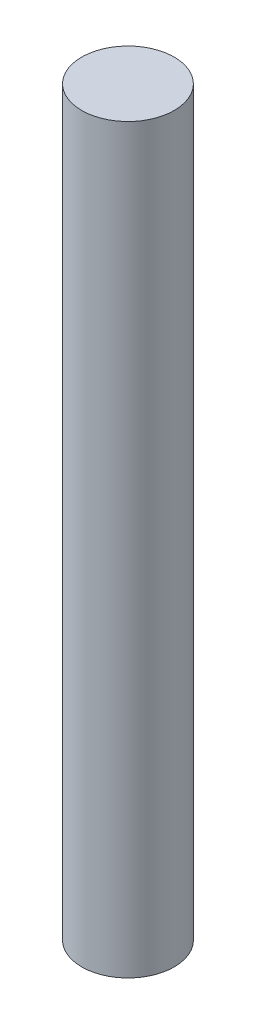
SolidWorks part; units mm, degrees
ref_plane "前视基准面" through (0, 0, 0) normal (0, 0, 1) x (1, 0, 0)
ref_plane "上视基准面" through (0, 0, 0) normal (0, 1, 0) x (1, 0, 0)
ref_plane "右视基准面" through (0, 0, 0) normal (1, 0, 0) x (0, 0, -1)
other "Configuration Table"
sketch "草图2" plane through (0, 0, 0) normal (0, 1, 0) x (1, 0, 0)
  circle A0 centre (0, 0) radius 4.99
  dimension "D1" = 9.98
extrude "凸台-拉伸1" add sketch "草图2" along normal blind 80
